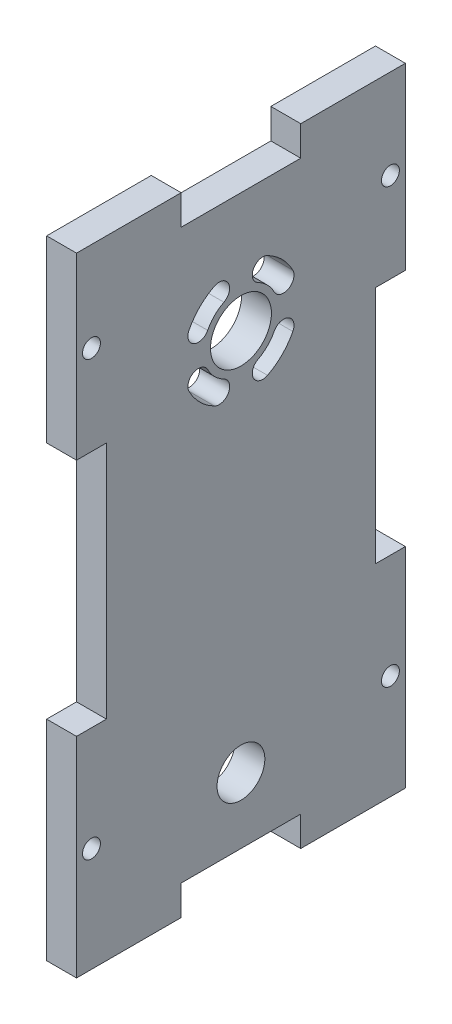
SolidWorks part; units mm, degrees
ref_plane "前视基准面" through (0, 0, 0) normal (0, 0, 1) x (1, 0, 0)
ref_plane "上视基准面" through (0, 0, 0) normal (0, 1, 0) x (1, 0, 0)
ref_plane "右视基准面" through (0, 0, 0) normal (1, 0, 0) x (0, 0, -1)
sketch "草图1" plane through (0, 0, 0) normal (1, 0, 0) x (0, 0, -1)
  line L0 (-37.5, 105) -> (-55, 105)
  line L1 (0, 0) -> (-17.5, 0)
  line L2 (0, 0) -> (0, 35)
  line L3 (0, 105) -> (-17.5, 105)
  line L4 (-55, 0) -> (-55, 35)
  line L5 (-55, 75) -> (-50, 75)
  line L6 (0, 75) -> (0, 105)
  line L7 (-55, 35) -> (-50, 35)
  line L8 (-50, 75) -> (-50, 35)
  line L9 (-55, 75) -> (-55, 105)
  line L10 (-37.5, 105) -> (-37.5, 100)
  line L11 (-37.5, 100) -> (-17.5, 100)
  line L12 (-17.5, 105) -> (-17.5, 100)
  line L13 (0, 75) -> (-5, 75)
  line L14 (-37.5, 0) -> (-55, 0)
  line L15 (0, 35) -> (-5, 35)
  line L16 (-5, 75) -> (-5, 35)
  line L17 (-27.5, 117.1856) -> (-27.5, -14.2539) construction
  line L18 (-37.5, 0) -> (-37.5, 5)
  line L19 (-37.5, 5) -> (-17.5, 5)
  line L20 (-17.5, 0) -> (-17.5, 5)
  circle A0 centre (-27.5, 16) radius 4
  circle A1 centre (-27.5, 80) radius 5.1
  arc A2 (-34.6237, 83.6405) -> (-31.147, 87.1204) centre (-27.5, 80) cw construction
  arc A3 (-31.9448, 88.6779) -> (-36.182, 84.4368) centre (-27.5, 80) ccw
  arc A4 (-30.3492, 85.5628) -> (-33.0654, 82.8441) centre (-27.5, 80) ccw
  arc A5 (-30.3492, 85.5628) -> (-31.9448, 88.6779) centre (-31.147, 87.1204) ccw
  arc A6 (-36.182, 84.4368) -> (-33.0654, 82.8441) centre (-34.6237, 83.6405) ccw
  arc A7 (-23.8595, 87.1237) -> (-20.3796, 83.647) centre (-27.5, 80) cw construction
  arc A8 (-18.8221, 84.4448) -> (-23.0632, 88.682) centre (-27.5, 80) ccw
  arc A9 (-21.9372, 82.8492) -> (-24.6559, 85.5654) centre (-27.5, 80) ccw
  arc A10 (-21.9372, 82.8492) -> (-18.8221, 84.4448) centre (-20.3796, 83.647) ccw
  arc A11 (-23.0632, 88.682) -> (-24.6559, 85.5654) centre (-23.8595, 87.1237) ccw
  arc A12 (-20.3763, 76.3595) -> (-23.853, 72.8796) centre (-27.5, 80) cw construction
  arc A13 (-23.0552, 71.3221) -> (-18.818, 75.5632) centre (-27.5, 80) ccw
  arc A14 (-24.6508, 74.4372) -> (-21.9346, 77.1559) centre (-27.5, 80) ccw
  arc A15 (-24.6508, 74.4372) -> (-23.0552, 71.3221) centre (-23.853, 72.8796) ccw
  arc A16 (-18.818, 75.5632) -> (-21.9346, 77.1559) centre (-20.3763, 76.3595) ccw
  arc A17 (-31.1405, 72.8763) -> (-34.6204, 76.353) centre (-27.5, 80) cw construction
  arc A18 (-36.1779, 75.5552) -> (-31.9368, 71.318) centre (-27.5, 80) ccw
  arc A19 (-33.0628, 77.1508) -> (-30.3441, 74.4346) centre (-27.5, 80) ccw
  arc A20 (-33.0628, 77.1508) -> (-36.1779, 75.5552) centre (-34.6204, 76.353) ccw
  arc A21 (-31.9368, 71.318) -> (-30.3441, 74.4346) centre (-31.1405, 72.8763) ccw
  circle A22 centre (-2.5, 90) radius 1.5
  circle A23 centre (-52.5, 90) radius 1.5
  circle A24 centre (-52.5, 17.5) radius 1.5
  circle A25 centre (-2.5, 17.5) radius 1.5
  point P27 (-27.5, 80)
  point P33 (-33.1594, 85.6543)
  point P39 (-21.8457, 85.6594)
  point P44 (0, 0)
  point P47 (-21.8406, 74.3457)
  point P54 (-33.1543, 74.3406)
  point P59 (-34.2186, 83.8929)
  point P60 (-27.5, 80)
  dimension "D16" = 11
  dimension "D17" = 10.2
  dimension "D20" = 1.75
  dimension "D19" = 0
  dimension "D21" = 20
  dimension "D22" = 4.919
  dimension "D25" = 15
  dimension "D1" = 105
  dimension "D2" = 55
  dimension "D3" = 5
  dimension "D4" = 5
  dimension "D5" = 5
  dimension "D6" = 20
  dimension "D7" = 40
  dimension "D8" = 40
  dimension "D9" = 20
  dimension "D10" = 5
  dimension "D11" = 17.5
  dimension "D12" = 17.5
  dimension "D13" = 35
  dimension "D14" = 35
  dimension "D15" = 22.5
  dimension "D18" = 8
  dimension "D23" = 4
  dimension "D24" = 64
  dimension "D26" = 15
  dimension "D27" = 15
  dimension "D28" = 17.5
  dimension "D29" = 17.5
  dimension "D30" = 2.5
  dimension "D31" = 2.5
  dimension "D32" = 2.5
  dimension "D33" = 2.5
extrude "凸台-拉伸1" add sketch "草图1" along normal blind 5
